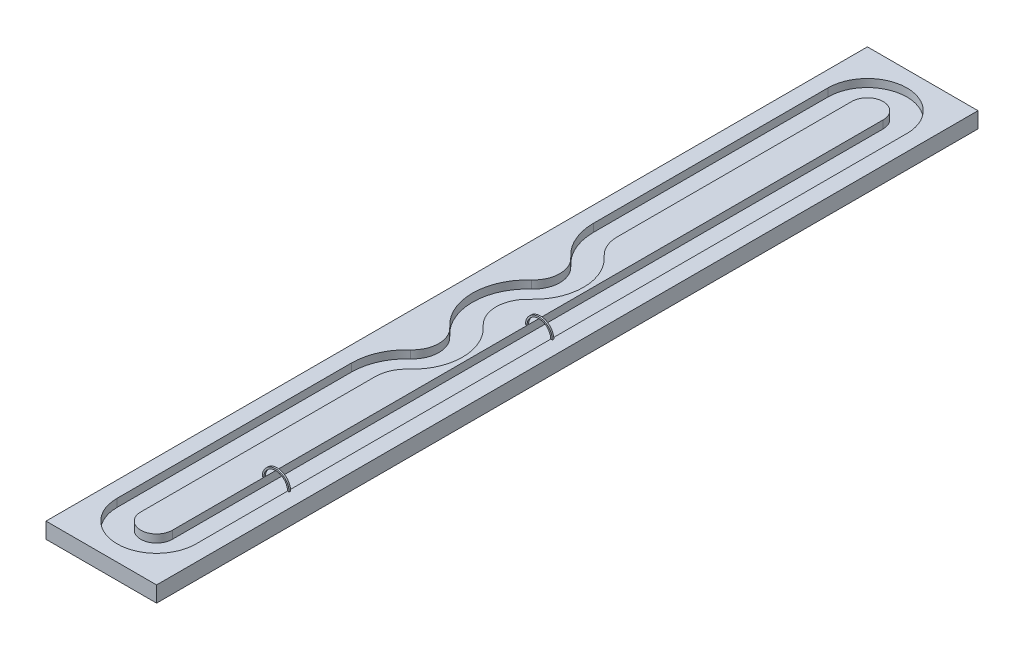
SolidWorks part; units mm, degrees
ref_plane "Front Plane" through (0, 0, 0) normal (0, 0, 1) x (1, 0, 0)
ref_plane "Top Plane" through (0, 0, 0) normal (0, 1, 0) x (1, 0, 0)
ref_plane "Right Plane" through (0, 0, 0) normal (1, 0, 0) x (0, 0, -1)
sketch "Sketch1" plane through (0, 0, 0) normal (0, 1, 0) x (1, 0, 0)
  line L1 (-3500, 51000) -> (3500, 51000)
  line L2 (-3500, 51000) -> (-3500, -1000)
  line L3 (-3500, -1000) -> (3500, -1000)
  line L4 (3500, 51000) -> (3500, -1000)
  point P4 (0, -1000)
  dimension "D1" = 52000
  dimension "D2" = 7000
  dimension "D3" = 1000
extrude "Boss-Extrude1" add sketch "Sketch1" along normal mid plane 1000
sketch "Sketch2" plane through (0, 500, 0) normal (0, 1, 0) x (1, 0, 0)
  line L0 (2500, 2500) -> (2500, 47500)
  line L1 (-2500, 47500) -> (-2500, 32660)
  line L2 (-2500, 17340) -> (-2500, 2500)
  line L3 (1000, 2500) -> (1000, 47500)
  line L4 (-1000, 47500) -> (-1000, 32660)
  line L5 (-1000, 17340) -> (-1000, 2500)
  arc A0 (2500, 47500) -> (-2500, 47500) centre (0, 47500) ccw
  arc A1 (-2500, 32660) -> (-1352.1019, 30071.7555) centre (991.8951, 32660) ccw
  arc A2 (-1352.1019, 30071.7555) -> (-1352.1019, 27588.2445) centre (-2476.6754, 28830) cw
  arc A3 (-1352.1019, 27588.2445) -> (-1352.1019, 22411.7555) centre (991.8951, 25000) ccw
  arc A5 (-2500, 2500) -> (2500, 2500) centre (0, 2500) ccw
  arc A6 (-1352.1019, 22411.7555) -> (-1352.1019, 19928.2445) centre (-2476.6754, 21170) cw
  arc A7 (-1352.1019, 19928.2445) -> (-2500, 17340) centre (991.8951, 17340) ccw
  arc A8 (1000, 47500) -> (-1000, 47500) centre (0, 47500) ccw
  arc A9 (-1000, 32660) -> (-345.2001, 31183.5778) centre (991.8951, 32660) ccw
  arc A10 (-345.2001, 31183.5778) -> (-345.2001, 26476.4222) centre (-2476.6754, 28830) cw
  arc A11 (-345.2001, 26476.4222) -> (-345.2001, 23523.5778) centre (991.8951, 25000) ccw
  arc A12 (-345.2001, 23523.5778) -> (-345.2001, 18816.4222) centre (-2476.6754, 21170) cw
  arc A13 (-345.2001, 18816.4222) -> (-1000, 17340) centre (991.8951, 17340) ccw
  arc A14 (-1000, 2500) -> (1000, 2500) centre (0, 2500) ccw
  arc A15 (-2500, 32660) -> (-1352.1019, 30071.7555) centre (991.8951, 32660) ccw construction
  arc A16 (-1352.1019, 30071.7555) -> (-1352.1019, 27588.2445) centre (-2476.6754, 28830) cw construction
  point P4 (0, 0)
  point P7 (-2476.6754, 28830)
  point P15 (0, 0)
  point P19 (0, 0)
  point P20 (0, 0)
  point P21 (0, 0)
  point P22 (3211.6595, 29072.6723)
  point P23 (0, 0)
  point P24 (0, 0)
  point P25 (0, 0)
  point P26 (0, 0)
  point P27 (0, 0)
  point P28 (0, 0)
  point P29 (0, 0)
  point P30 (2036.9588, 32660)
  point P31 (2335.6407, 32660)
  point P32 (1173.5542, 32660)
  point P50 (0, 0)
  point P52 (0, 0)
  point P54 (0, 0)
  dimension "D2" = 2500
  dimension "D5" = 3830
  dimension "D8" = 1500
  dimension "D4" = 3830
  dimension "D1" = 5000
  dimension "D3" = 45000
  dimension "D6" = 3830
  dimension "D7" = 3830
extrude "Cut-Extrude1" cut sketch "Sketch2" against normal blind 500
ref_plane "Plane1" through (0, 0, -25000) normal (0, 0, -1) x (-1, 0, 0)
sketch "Sketch3" plane through (0, 0, -25000) normal (0, 0, -1) x (-1, 0, 0)
  line L0 (-1000, 500) -> (-900, 500)
  line L1 (1000, 500) -> (-1000, 500) construction
  line L2 (-3500, 500) -> (3500, 500) construction
  line L3 (-2600, 500) -> (-2500, 500)
  arc A0 (-1000, 500) -> (-2500, 500) centre (-1750, 500) ccw
  arc A1 (-900, 500) -> (-2600, 500) centre (-1750, 500) ccw
  dimension "D2" = 750
  dimension "D1" = 100
extrude "Boss-Extrude2" add sketch "Sketch3" along normal mid plane 100
pattern_linear "LPattern1" count 2 spacing 16660 along (0, 0, 1) of "Boss-Extrude2"
